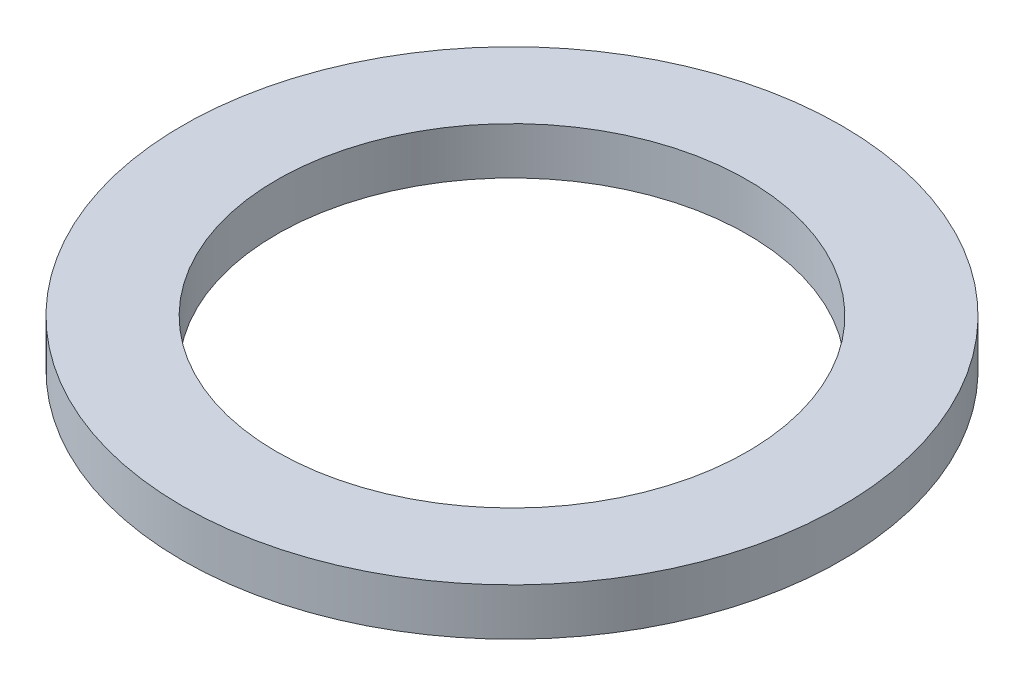
SolidWorks part; units mm, degrees
ref_plane "Front Plane" through (0, 0, 0) normal (0, 0, 1) x (1, 0, 0)
ref_plane "Top Plane" through (0, 0, 0) normal (0, 1, 0) x (1, 0, 0)
ref_plane "Right Plane" through (0, 0, 0) normal (1, 0, 0) x (0, 0, -1)
sketch "Sketch1" plane through (0, 0, 0) normal (0, 1, 0) x (1, 0, 0)
  circle A0 centre (0, 0) radius 2.5
  circle A1 centre (0, 0) radius 3.5
  dimension "D1" = 7
  dimension "D2" = 5
extrude "Boss-Extrude1" add sketch "Sketch1" along normal mid plane 0.5
